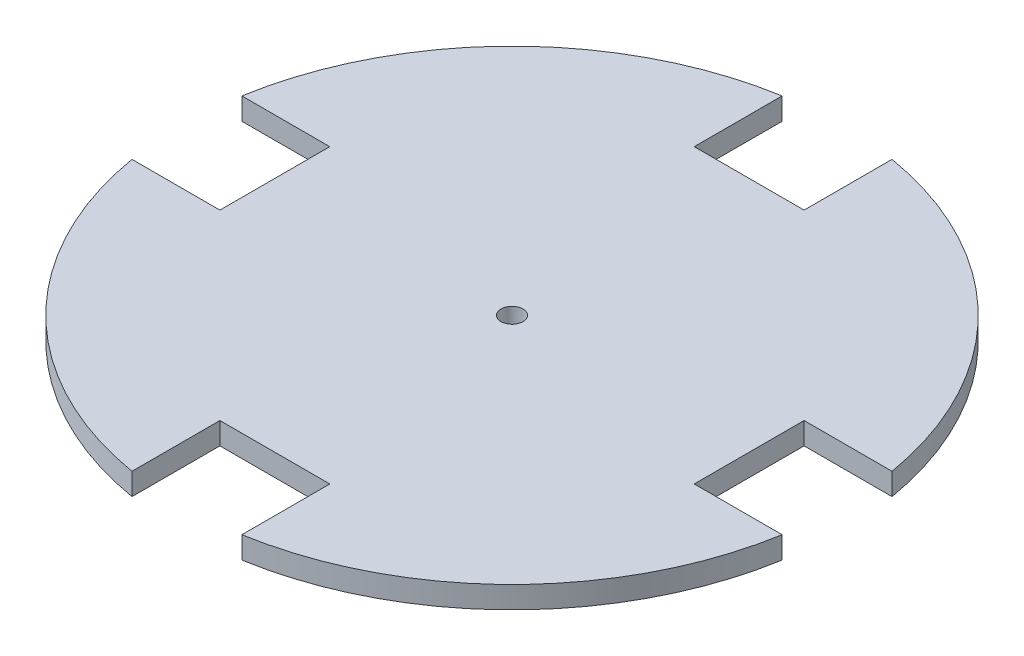
SolidWorks part; units mm, degrees
ref_plane "Front Plane" through (0, 0, 0) normal (0, 0, 1) x (1, 0, 0)
ref_plane "Top Plane" through (0, 0, 0) normal (0, 1, 0) x (1, 0, 0)
ref_plane "Right Plane" through (0, 0, 0) normal (1, 0, 0) x (0, 0, -1)
sketch "Sketch2" plane through (0, 0, 0) normal (0, 1, 0) x (1, 0, 0)
  line L0 (0, 85.8711) -> (0, -84.6301) construction
  line L1 (-105.2921, 0) -> (112.1885, 0) construction
  line L2 (107.902, 25) -> (147.902, 25)
  line L3 (-25, 107.902) -> (25, 107.902)
  line L4 (-25, 107.902) -> (-25, 147.902)
  line L6 (25, 107.902) -> (25, 147.902)
  line L7 (-25, 107.902) -> (25, 147.902) construction
  line L8 (-25, 147.902) -> (25, 107.902) construction
  line L9 (107.902, 25) -> (107.902, -25)
  line L10 (107.902, -25) -> (147.902, -25)
  line L12 (25, -107.902) -> (25, -147.902)
  line L13 (25, -107.902) -> (-25, -107.902)
  line L14 (-25, -107.902) -> (-25, -147.902)
  line L16 (-107.902, -25) -> (-147.902, -25)
  line L17 (-107.902, -25) -> (-107.902, 25)
  line L18 (-107.902, 25) -> (-147.902, 25)
  arc A0 (-25, 147.902) -> (-147.902, 25) centre (0, 0) ccw
  arc A1 (147.902, 25) -> (25, 147.902) centre (0, 0) ccw
  arc A2 (25, -147.902) -> (147.902, -25) centre (0, 0) ccw
  arc A3 (-147.902, -25) -> (-25, -147.902) centre (0, 0) ccw
  circle A4 centre (0, 0) radius 5
  point P7 (0, 127.902)
  point P12 (54.9878, 0)
  point P17 (0, -63.3174)
  point P22 (-65.3255, 0)
  point P30 (0, 0)
  dimension "D1" = 4
  dimension "200" = 300
  dimension "D4" = 10
  dimension "D2" = 40
  dimension "D3" = 50
extrude "Boss-Extrude1" add sketch "Sketch2" along normal mid plane 10
